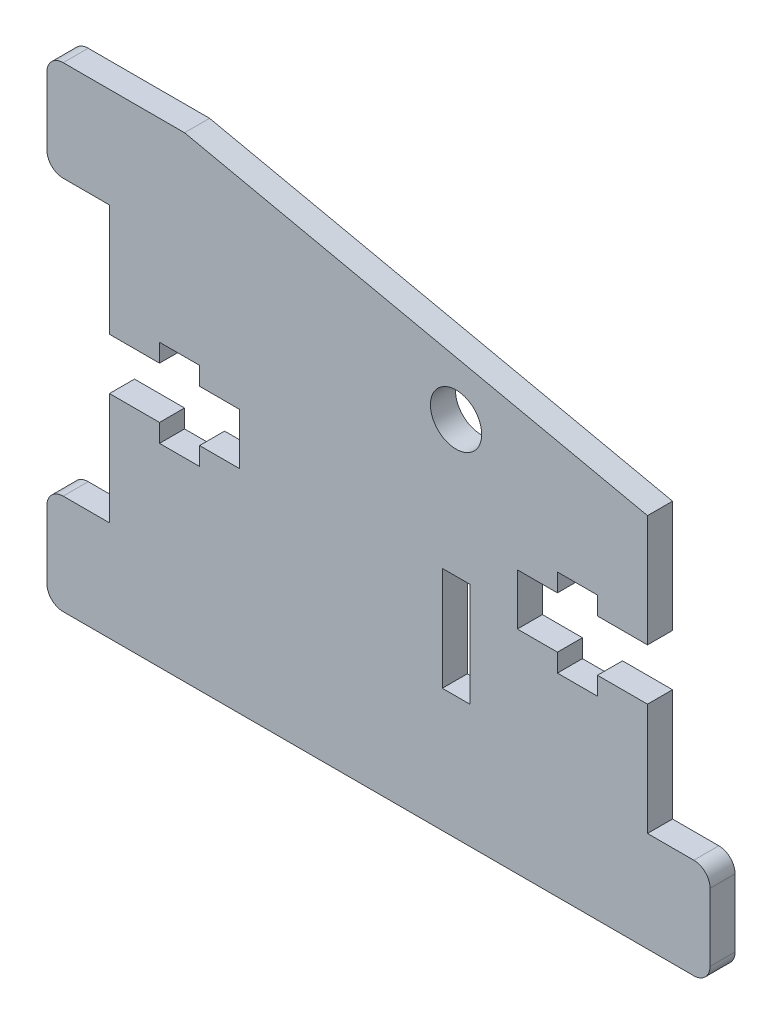
SolidWorks part; units mm, degrees
ref_plane "前视基准面" through (0, 0, 0) normal (0, 0, 1) x (1, 0, 0)
ref_plane "上视基准面" through (0, 0, 0) normal (0, 1, 0) x (1, 0, 0)
ref_plane "右视基准面" through (0, 0, 0) normal (1, 0, 0) x (0, 0, -1)
sketch "草图1" plane through (0, 0, 0) normal (0, 0, 1) x (1, 0, 0)
  line L0 (-35.5238, 30.2399) -> (-30.5238, 30.2399)
  line L1 (-35.5238, 30.2399) -> (-35.5238, 38.2399)
  line L2 (-35.5238, 38.2399) -> (-30.5238, 38.2399)
  line L3 (-30.5238, 38.2399) -> (-30.5238, 47.1899)
  line L4 (-30.5238, 47.1899) -> (-26.5238, 47.1899)
  line L5 (-26.5238, 47.1899) -> (-26.5238, 45.7399)
  line L6 (-26.5238, 45.7399) -> (-23.3238, 45.7399)
  line L7 (-23.3238, 45.7399) -> (-23.3238, 47.1899)
  line L8 (-23.3238, 47.1899) -> (-20.1238, 47.1899)
  line L9 (-20.1238, 47.1899) -> (-20.1238, 51.2899)
  line L10 (-20.1238, 51.2899) -> (-23.3238, 51.2899)
  line L11 (-23.3238, 51.2899) -> (-23.3238, 52.7399)
  line L12 (-23.3238, 52.7399) -> (-26.5238, 52.7399)
  line L13 (-26.5238, 52.7399) -> (-26.5238, 51.2899)
  line L14 (-26.5238, 51.2899) -> (-30.5238, 51.2899)
  line L15 (-30.5238, 60.2399) -> (-30.5238, 51.2899)
  line L16 (-20.1238, 49.2399) -> (-21.8238, 49.2399) construction
  line L17 (-35.5238, 60.2399) -> (-30.5238, 60.2399)
  line L18 (-35.5238, 68.2399) -> (-35.5238, 60.2399)
  line L19 (-35.5238, 68.2399) -> (-30.5238, 68.2399)
  line L20 (-30.5238, 30.2399) -> (12.4762, 30.2399)
  line L21 (-9.0238, 30.2399) -> (-9.0238, 59.2399) construction
  line L22 (12.4762, 60.2399) -> (12.4762, 51.2899)
  line L23 (2.0762, 49.2399) -> (3.7761, 49.2399) construction
  line L24 (8.4762, 51.2899) -> (12.4762, 51.2899)
  line L25 (8.4762, 52.7399) -> (8.4762, 51.2899)
  line L26 (5.2762, 52.7399) -> (8.4762, 52.7399)
  line L27 (5.2762, 51.2899) -> (5.2762, 52.7399)
  line L28 (2.0762, 51.2899) -> (5.2762, 51.2899)
  line L29 (2.0762, 47.1899) -> (2.0762, 51.2899)
  line L30 (5.2762, 47.1899) -> (2.0762, 47.1899)
  line L31 (5.2762, 45.7399) -> (5.2762, 47.1899)
  line L32 (8.4762, 45.7399) -> (5.2762, 45.7399)
  line L33 (8.4762, 47.1899) -> (8.4762, 45.7399)
  line L34 (12.4762, 47.1899) -> (8.4762, 47.1899)
  line L35 (12.4762, 38.2399) -> (12.4762, 47.1899)
  line L36 (17.4762, 38.2399) -> (12.4762, 38.2399)
  line L37 (17.4762, 30.2399) -> (17.4762, 38.2399)
  line L38 (17.4762, 30.2399) -> (12.4762, 30.2399)
  line L39 (12.4762, 60.2399) -> (-24.5238, 68.2399)
  line L40 (-24.5238, 68.2399) -> (-30.5238, 68.2399)
  line L41 (-3.9238, 48.3899) -> (-1.7238, 48.3899)
  line L42 (-10.1238, 48.3899) -> (-7.9238, 48.3899) construction
  line L43 (-10.1238, 48.3899) -> (-10.1238, 40.0899) construction
  line L44 (-10.1238, 40.0899) -> (-7.9238, 40.0899) construction
  line L45 (-7.9238, 48.3899) -> (-7.9238, 40.0899) construction
  line L46 (-10.1238, 48.3899) -> (-7.9238, 40.0899) construction
  line L47 (-10.1238, 40.0899) -> (-7.9238, 48.3899) construction
  line L48 (-3.9238, 48.3899) -> (-3.9238, 40.0899)
  line L49 (-3.9238, 40.0899) -> (-1.7238, 40.0899)
  line L50 (-1.7238, 48.3899) -> (-1.7238, 40.0899)
  line L51 (-3.9238, 48.3899) -> (-1.7238, 40.0899) construction
  line L52 (-3.9238, 40.0899) -> (-1.7238, 48.3899) construction
  circle A0 centre (-9.0238, 59.2399) radius 2.05 construction
  circle A1 centre (-2.8238, 59.2399) radius 2.05
  point P24 (-9.0238, 44.2399)
  dimension "D9" = 29
  dimension "D1" = 3.2
  dimension "D2" = 4.1
  dimension "D4" = 11
  dimension "D5" = 5
  dimension "D6" = 8
  dimension "D7" = 43
  dimension "D8" = 4
  dimension "D10" = 15
  dimension "D11" = 2.2
  dimension "D12" = 8.3
extrude "凸台-拉伸1" add sketch "草图1" along normal blind 2
fillet "圆角1" radius 1.3 6 edges at (17.4762, 38.2399, 1) (17.4762, 30.2399, 1) (-35.5238, 68.2399, 1) (-35.5238, 60.2399, 1) (-35.5238, 38.2399, 1) (-35.5238, 30.2399, 1)
sketch "草图2" plane through (-30.5238, 0, 0) normal (-1, 0, 0) x (0, 0, 1)
  line L0 (1, 51.2899) -> (1, 47.1899)
  line L1 (2, 51.2899) -> (0, 51.2899) construction
  line L2 (2, 47.1899) -> (0, 47.1899) construction
  circle A0 centre (1, 49.2399) radius 2.05
